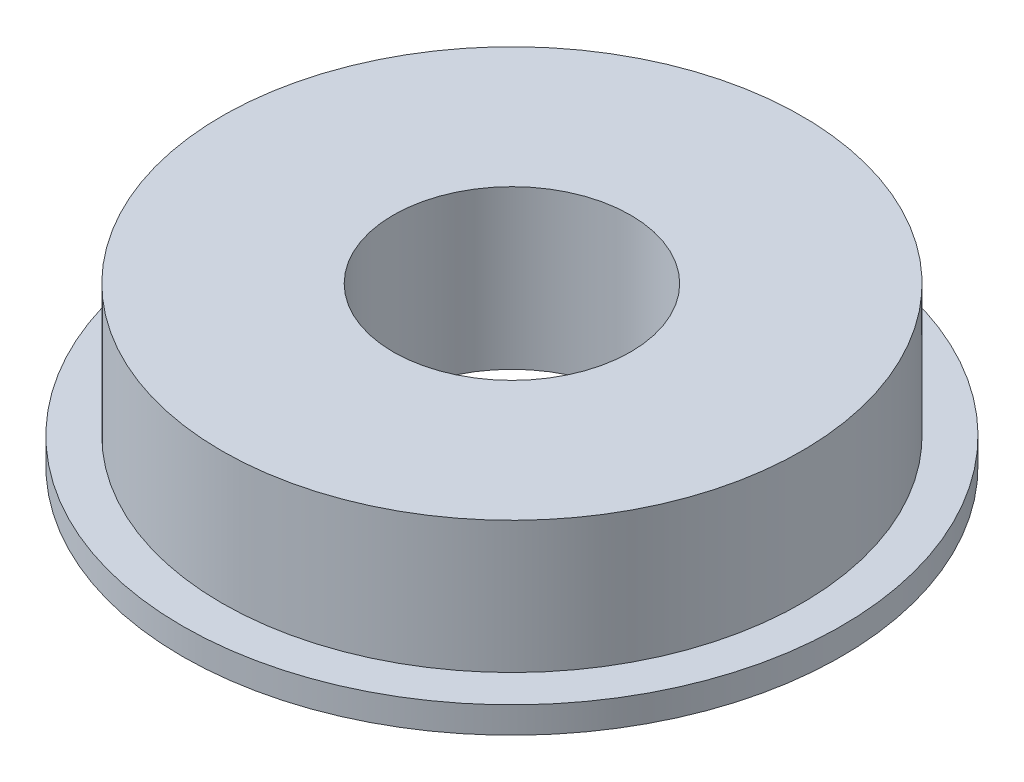
SolidWorks part; units mm, degrees
ref_plane "Front Plane" through (0, 0, 0) normal (0, 0, 1) x (1, 0, 0)
ref_plane "Top Plane" through (0, 0, 0) normal (0, 1, 0) x (1, 0, 0)
ref_plane "Right Plane" through (0, 0, 0) normal (1, 0, 0) x (0, 0, -1)
sketch "Sketch1" plane through (0, 0, 0) normal (0, 1, 0) x (1, 0, 0)
  circle A0 centre (0, 0) radius 12.5
  circle A1 centre (0, 0) radius 4.5
extrude "Boss-Extrude1" add sketch "Sketch1" along normal blind 1
sketch "Sketch2" plane through (0, 1, 0) normal (0, 1, 0) x (1, 0, 0)
  circle A0 centre (0, 0) radius 11
extrude "Boss-Extrude2" add sketch "Sketch2" along normal blind 5
sketch "Sketch3" plane through (0, 1, 0) normal (0, -1, 0) x (1, 0, 0)
  circle A0 centre (0, 0) radius 4.5
extrude "Cut-Extrude1" cut sketch "Sketch3" against normal through all both and the other way through all
